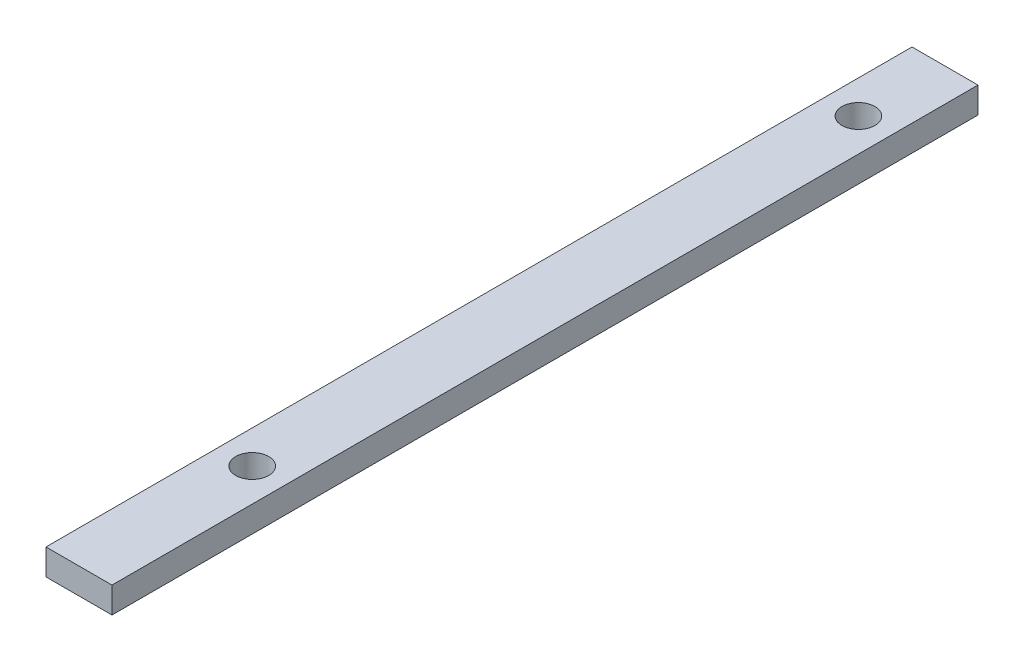
SolidWorks part; units mm, degrees
ref_plane "Front" through (0, 0, 0) normal (0, 0, 1) x (1, 0, 0)
ref_plane "Top" through (0, 0, 0) normal (0, 1, 0) x (1, 0, 0)
ref_plane "Right" through (0, 0, 0) normal (1, 0, 0) x (0, 0, -1)
sketch "Sketch1" plane through (0, 0, 0) normal (0, 1, 0) x (1, 0, 0)
  line L1 (0, 0) -> (7.62, 0)
  line L2 (0, 0) -> (0, 100)
  line L3 (0, 100) -> (7.62, 100)
  line L4 (7.62, 0) -> (7.62, 100)
  dimension "D1" = 100
  dimension "D2" = 7.62
extrude "Boss-Extrude1" add sketch "Sketch1" along normal blind 3
sketch "Sketch2" plane through (0, 3, 0) normal (0, 1, 0) x (1, 0, 0)
  line L0 (3.81, 100) -> (3.81, 0) construction
  line L1 (7.62, 100) -> (0, 100) construction
  line L2 (0, 0) -> (7.62, 0) construction
  circle A2 centre (3.81, 90) radius 1.905
  circle A3 centre (3.81, 20) radius 1.905
  dimension "D1" = 70
  dimension "D4" = 3.81
  dimension "D5" = 20
extrude "Cut-Extrude1" cut sketch "Sketch2" against normal through all
